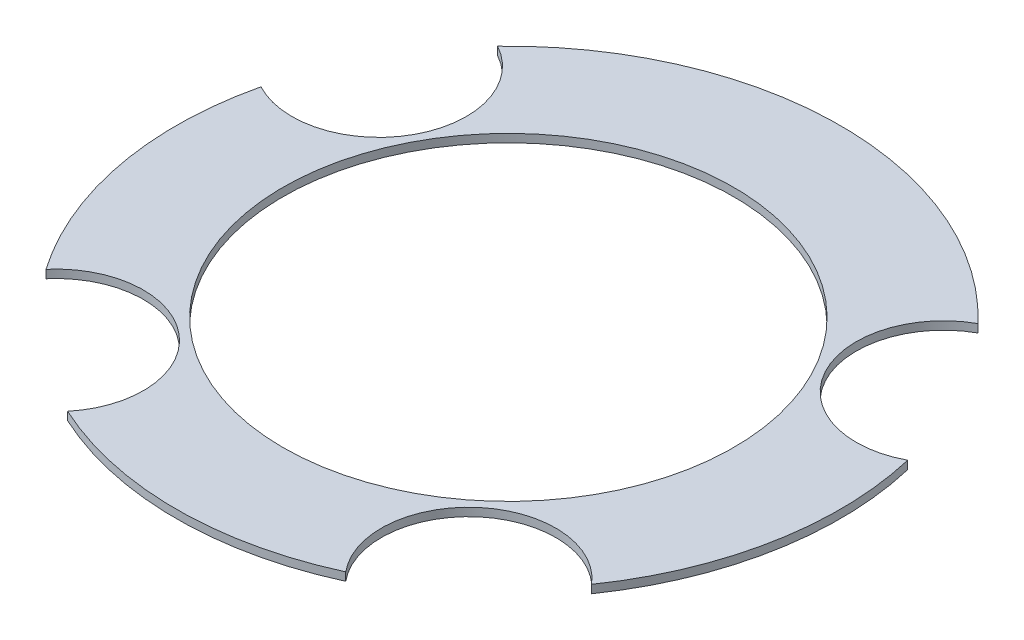
SolidWorks part; units mm, degrees
ref_plane "Front Plane" through (0, 0, 0) normal (0, 0, 1) x (1, 0, 0)
ref_plane "Top Plane" through (0, 0, 0) normal (0, 1, 0) x (1, 0, 0)
ref_plane "Right Plane" through (0, 0, 0) normal (1, 0, 0) x (0, 0, -1)
sketch "Sketch1" plane through (0, 0, 0) normal (0, 1, 0) x (-1, 0, 0)
  line L0 (-29.3916, 44.1494) -> (-29.3916, -38.9266) construction
  line L1 (-67.9296, 2.6114) -> (11.1464, 2.6114) construction
  circle A0 centre (-29.3916, 2.6114) radius 40.538
  circle A2 centre (-29.3916, 2.6114) radius 27.506
  dimension "D2" = 81.076
  dimension "D1" = 55.012
extrude "Boss-Extrude1" add sketch "Sketch1" along normal blind 1
sketch "Sketch3" plane through (0, 1, 0) normal (0, 1, 0) x (1, 0, 0)
  line L0 (29.3916, 37.9266) -> (29.3916, 24.8946) construction
  circle A0 centre (29.3916, -2.6114) radius 40.538 construction
  circle A1 centre (29.3916, -2.6114) radius 27.506 construction
sketch "Sketch4" plane through (0, 0, 0) normal (0, -1, 0) x (1, 0, 0)
  circle A0 centre (4.2238, 32.6285) radius 10.65
  circle A1 centre (54.5593, 32.6285) radius 10.65
  circle A2 centre (63.8297, -16.0557) radius 10.65
  circle A3 centre (-5.0466, -16.0557) radius 10.65
extrude "Cut-Extrude1" cut sketch "Sketch4" against normal blind 1
sketch "Sketch9" plane through (0, 1, 0) normal (0, 1, 0) x (1, 0, 0)
  line L0 (29.3916, 37.9266) -> (29.3916, -43.1494) construction
  arc A0 (58.7037, 25.391) -> (0.0795, 25.391) centre (29.3916, -2.6114) ccw construction
  arc A1 (12.4219, -39.4266) -> (46.3612, -39.4266) centre (29.3916, -2.6114) ccw construction
